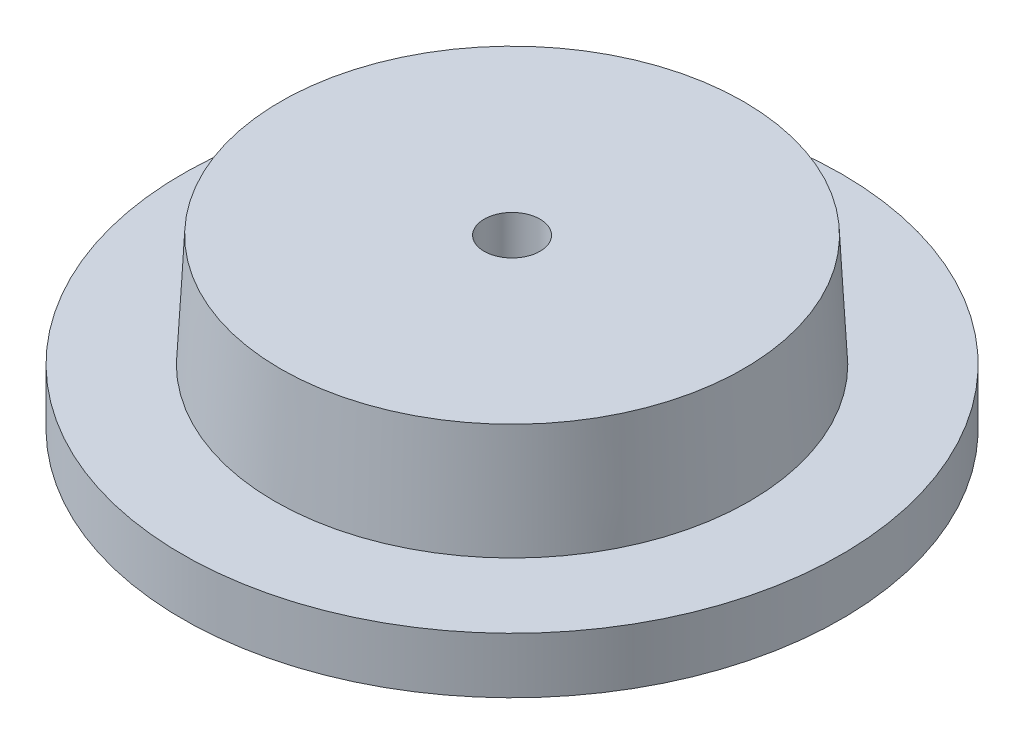
SolidWorks part; units mm, degrees
ref_plane "Front Plane" through (0, 0, 0) normal (0, 0, 1) x (1, 0, 0)
ref_plane "Top Plane" through (0, 0, 0) normal (0, 1, 0) x (1, 0, 0)
ref_plane "Right Plane" through (0, 0, 0) normal (1, 0, 0) x (0, 0, -1)
sketch "Sketch1" plane through (0, 0, 0) normal (0, 1, 0) x (1, 0, 0)
  circle A0 centre (0, 0) radius 2.125
extrude "Boss-Extrude1" add sketch "Sketch1" along normal blind 1 draft 3
sketch "Sketch2" plane through (0, 0, 0) normal (0, -1, 0) x (1, 0, 0)
  circle A0 centre (0, 0) radius 2.95
  dimension "D1" = 5.9
extrude "Boss-Extrude2" add sketch "Sketch2" along normal blind 0.5
sketch "Sketch3" plane through (0, 1, 0) normal (0, 1, 0) x (1, 0, 0)
  circle A0 centre (0, 0) radius 0.25
extrude "Cut-Extrude1" cut sketch "Sketch3" against normal through all
